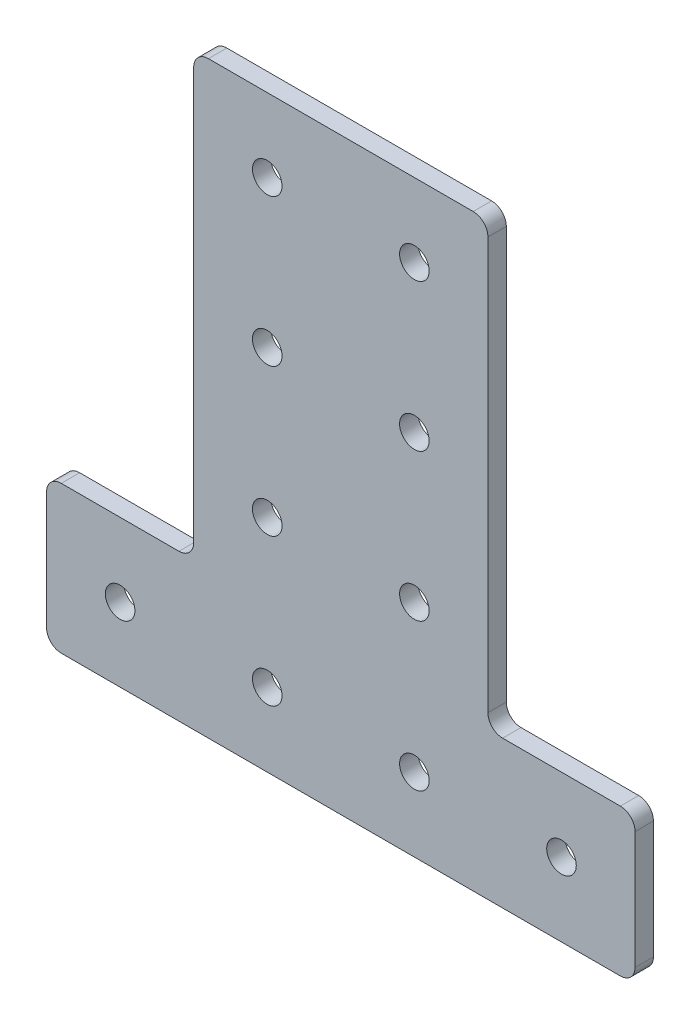
SolidWorks part; units mm, degrees
material "6061 Alloy"
ref_plane "Front" through (0, 0, 0) normal (0, 0, 1) x (1, 0, 0)
ref_plane "Top" through (0, 0, 0) normal (0, 1, 0) x (1, 0, 0)
ref_plane "Right" through (0, 0, 0) normal (1, 0, 0) x (0, 0, -1)
sketch "Sketch1" plane through (0, 0, 0) normal (0, 0, 1) x (1, 0, 0)
  line L0 (-76.2, 25.4) -> (-101.6, 25.4)
  line L1 (0, 0) -> (-101.6, 0)
  line L2 (0, 0) -> (0, 25.4)
  line L3 (0, 25.4) -> (-25.4, 25.4)
  line L4 (-101.6, 0) -> (-101.6, 25.4)
  line L6 (-76.2, 25.4) -> (-76.2, 101.6)
  line L7 (-76.2, 101.6) -> (-25.4, 101.6)
  line L8 (-25.4, 25.4) -> (-25.4, 101.6)
  dimension "D1" = 25.4
  dimension "D2" = 50.8
  dimension "D3" = 25.4
  dimension "D4" = 25.4
  dimension "D5" = 76.2
extrude "Boss-Extrude1" add sketch "Sketch1" along normal blind 3.175
fillet "Fillet1" radius 2.54 8 edges at (-101.6, 0, 1.5875) (-101.6, 25.4, 1.5875) (-76.2, 101.6, 1.5875) (-25.4, 101.6, 1.5875) (0, 0, 1.5875) (0, 25.4, 1.5875) (-76.2, 25.4, 1.5875) (-25.4, 25.4, 1.5875)
hole_wizard "#10 Clearance Hole1" positions "Sketch3" profile "Sketch4" hole size "#10" standard "ANSI Inch"
sketch "Sketch3" plane through (0, 0, 3.175) normal (0, 0, 1) x (1, 0, 0)
  line L0 (-2.54, 25.4) -> (-22.86, 25.4) construction
  line L1 (-76.2, 99.06) -> (-76.2, 27.94) construction
  point P0 (-63.5, 88.9)
  point P2 (-63.5, 63.5)
  point P4 (-63.5, 38.1)
  point P13 (-38.1, 88.9)
  point P15 (-38.1, 63.5)
  point P17 (-38.1, 38.1)
  point P21 (0, 0)
  point P22 (0, 0)
  point P23 (0, 0)
  dimension "D1" = 12.7
  dimension "D2" = 25.4
  dimension "D3" = 25.4
  dimension "D4" = 12.7
  dimension "D5" = 25.4
sketch "Sketch4" plane through (-63.5, 88.9, 3.175) normal (1, 0, 0) x (0, -1, 0)
  line L0 (0, 0) -> (0, 4.7078)
  line L1 (0, 4.7078) -> (2.5527, 3.174)
  line L2 (2.5527, 3.174) -> (2.5527, 0)
  line L5 (2.5527, 0) -> (0, 0)
  line L10 (0, 4.7078) -> (-2.5527, 3.174) construction
  line L11 (0, -6.35) -> (0, 107.95) construction
  dimension "Hole Dia." = 5.1054
  dimension "Hole Depth" = 3.174
  dimension "Drill Angle" = 118
hole_wizard "#10 Clearance Hole2" positions "Sketch5" profile "Sketch6" hole size "#10" standard "ANSI Inch"
sketch "Sketch5" plane through (0, 0, 0) normal (0, 0, 1) x (1, 0, 0)
  line L0 (0, 2.54) -> (0, 22.86) construction
  line L1 (-101.6, 22.86) -> (-101.6, 2.54) construction
  line L2 (-99.06, 0) -> (-2.54, 0) construction
  point P0 (-88.9, 12.7)
  point P2 (-63.5, 12.7)
  point P4 (-38.1, 12.7)
  point P6 (-12.7, 12.7)
  point P15 (0, 0)
  dimension "D1" = 25.4
  dimension "D2" = 25.4
  dimension "D3" = 12.7
  dimension "D4" = 12.7
  dimension "D5" = 12.7
sketch "Sketch6" plane through (-88.9, 12.7, 0) normal (1, 0, 0) x (0, 1, 0)
  line L0 (0, 0) -> (0, 4.7078)
  line L1 (0, 4.7078) -> (2.5527, 3.174)
  line L2 (2.5527, 3.174) -> (2.5527, 0)
  line L5 (2.5527, 0) -> (0, 0)
  line L10 (0, 4.7078) -> (-2.5527, 3.174) construction
  line L11 (0, -6.35) -> (0, 107.95) construction
  dimension "Hole Dia." = 5.1054
  dimension "Hole Depth" = 3.174
  dimension "Drill Angle" = 118
